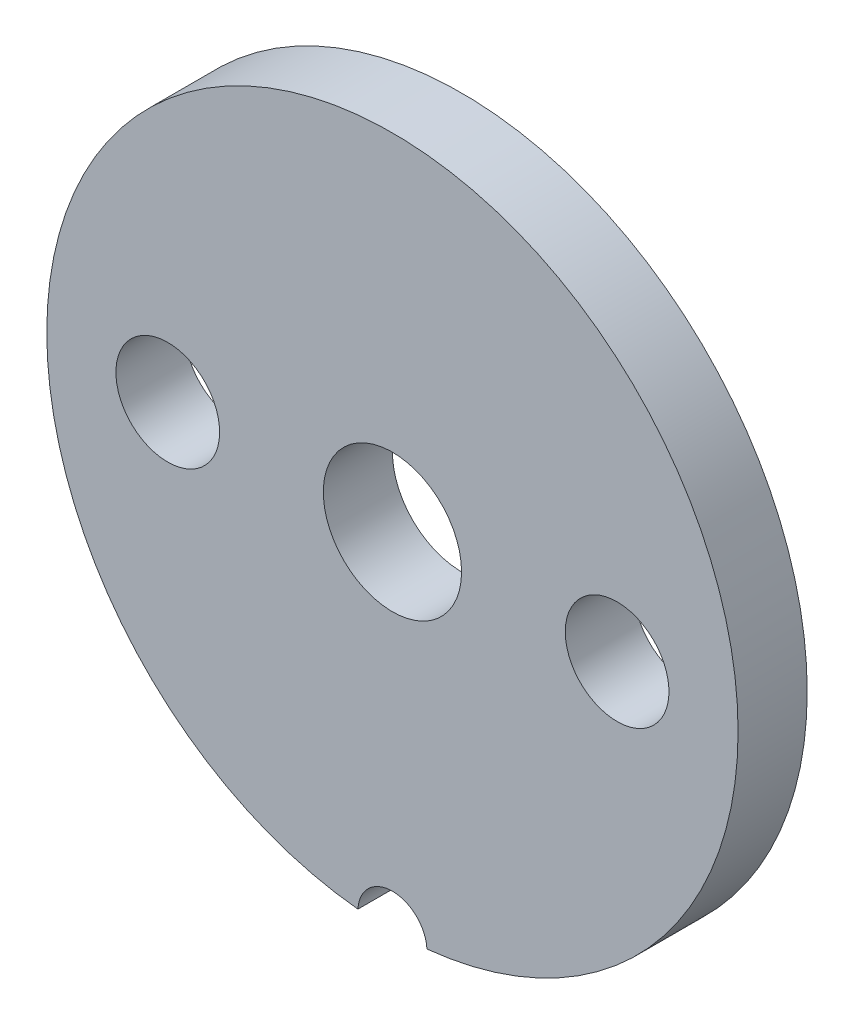
SolidWorks part; units mm, degrees
ref_plane "前视基准面" through (0, 0, 0) normal (0, 0, 1) x (1, 0, 0)
ref_plane "上视基准面" through (0, 0, 0) normal (0, 1, 0) x (1, 0, 0)
ref_plane "右视基准面" through (0, 0, 0) normal (1, 0, 0) x (0, 0, -1)
sketch "草图1" plane through (0, 0, 0) normal (0, 0, 1) x (1, 0, 0)
  line L0 (0.7836, -0.3918) -> (0.7836, -3.8918) construction
  line L1 (0.7836, -3.8918) -> (-5.7164, -3.8918) construction
  circle A0 centre (-5.7164, -3.8918) radius 1.5
  circle A1 centre (7.2836, -3.8918) radius 1.5
  circle A2 centre (0.7836, -3.8918) radius 2
  circle A4 centre (0.7836, -3.8918) radius 10
  dimension "D1" = 3.5
  dimension "D2" = 6.5
extrude "凸台-拉伸1" add sketch "草图1" along normal blind 2
sketch "草图2" plane through (0, 0, 2) normal (0, 0, 1) x (1, 0, 0)
  circle A0 centre (0.7836, -13.8918) radius 1
  circle A1 centre (0.7836, -3.8918) radius 10 construction
extrude "切除-拉伸1" cut sketch "草图2" against normal blind 10
